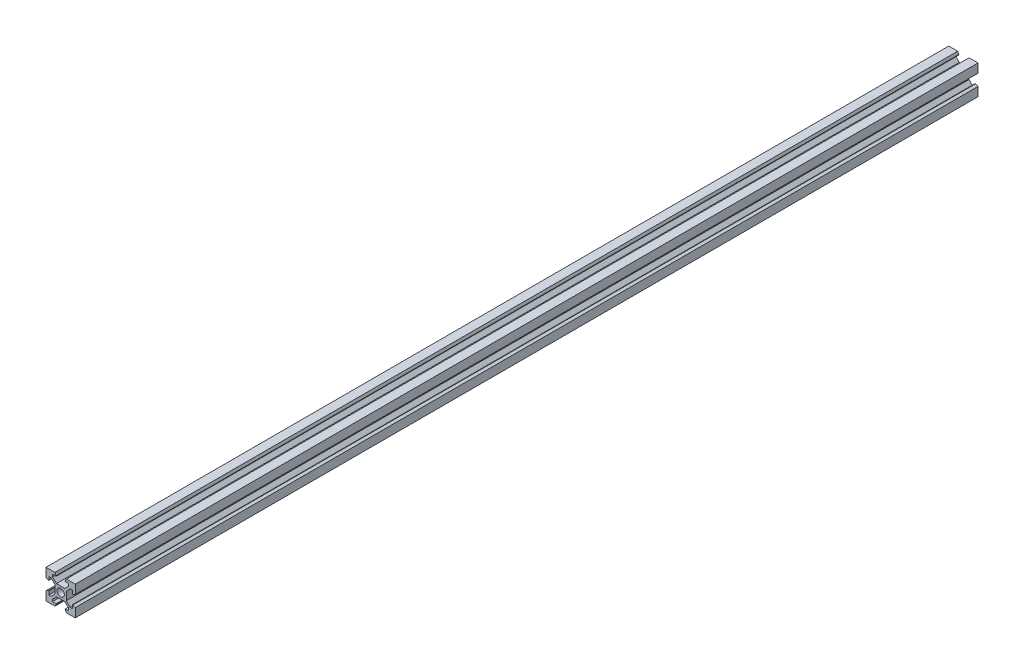
SolidWorks part; units mm, degrees
ref_plane "Front Plane" through (0, 0, 0) normal (0, 0, 1) x (1, 0, 0)
ref_plane "Top Plane" through (0, 0, 0) normal (0, 1, 0) x (1, 0, 0)
ref_plane "Right Plane" through (0, 0, 0) normal (1, 0, 0) x (0, 0, -1)
sketch "Sketch1" plane through (0, 0, 0) normal (0, 0, 1) x (1, 0, 0)
  line L0 (0, 20) -> (0, 13.8958)
  line L1 (0, 0) -> (20, 0)
  line L2 (0, 0) -> (0, 20)
  line L3 (0, 20) -> (20, 20)
  line L4 (20, 0) -> (20, 20)
  line L5 (0, 13.8958) -> (1.56, 13.1)
  line L6 (1.56, 13.1) -> (1.9, 13.1)
  line L7 (1.9, 13.1) -> (1.9, 15.5)
  line L8 (1.9, 15.5) -> (3.4393, 15.5)
  line L9 (3.4393, 15.5) -> (6.2656, 12.6737)
  line L10 (6.2656, 12.6737) -> (7.3263, 13.7344)
  line L11 (7.3263, 13.7344) -> (4.5, 16.5607)
  line L12 (4.5, 16.5607) -> (4.5, 18.1)
  line L13 (4.5, 18.1) -> (6.9, 18.1)
  line L14 (6.9, 18.1) -> (6.9, 18.44)
  line L15 (6.9, 18.44) -> (6.1, 20)
  line L16 (6.1, 20) -> (0, 20)
  line L17 (10, 10) -> (6.1, 13.9)
  line L18 (6.1, 6.1) -> (13.9, 6.1)
  line L19 (6.1, 6.1) -> (6.1, 13.9)
  line L20 (6.1, 13.9) -> (13.9, 13.9)
  line L21 (13.9, 6.1) -> (13.9, 13.9)
  line L22 (6.796, 13.204) -> (4.0494, 15.9506)
  line L23 (10, 10) -> (10, 24.9145) construction
  line L24 (13.1, 18.44) -> (13.9, 20)
  line L25 (13.1, 18.1) -> (13.1, 18.44)
  line L26 (15.5, 18.1) -> (13.1, 18.1)
  line L27 (15.5, 16.5607) -> (15.5, 18.1)
  line L28 (12.6737, 13.7344) -> (15.5, 16.5607)
  line L29 (13.7344, 12.6737) -> (12.6737, 13.7344)
  line L30 (16.5607, 15.5) -> (13.7344, 12.6737)
  line L31 (18.1, 15.5) -> (16.5607, 15.5)
  line L32 (18.1, 13.1) -> (18.1, 15.5)
  line L33 (18.44, 13.1) -> (18.1, 13.1)
  line L34 (20, 13.8958) -> (18.44, 13.1)
  line L35 (10, 10) -> (22.1718, 10)
  line L36 (20, 6.1042) -> (18.44, 6.9)
  line L37 (18.44, 6.9) -> (18.1, 6.9)
  line L38 (18.1, 6.9) -> (18.1, 4.5)
  line L39 (18.1, 4.5) -> (16.5607, 4.5)
  line L40 (16.5607, 4.5) -> (13.7344, 7.3263)
  line L41 (13.7344, 7.3263) -> (12.6737, 6.2656)
  line L42 (12.6737, 6.2656) -> (15.5, 3.4393)
  line L43 (15.5, 3.4393) -> (15.5, 1.9)
  line L44 (15.5, 1.9) -> (13.1, 1.9)
  line L45 (13.1, 1.9) -> (13.1, 1.56)
  line L46 (13.1, 1.56) -> (13.9, 0)
  line L47 (6.9, 1.56) -> (6.1, 0)
  line L48 (6.9, 1.9) -> (6.9, 1.56)
  line L49 (4.5, 1.9) -> (6.9, 1.9)
  line L50 (4.5, 3.4393) -> (4.5, 1.9)
  line L51 (7.3263, 6.2656) -> (4.5, 3.4393)
  line L52 (6.2656, 7.3263) -> (7.3263, 6.2656)
  line L53 (3.4393, 4.5) -> (6.2656, 7.3263)
  line L54 (1.9, 4.5) -> (3.4393, 4.5)
  line L55 (1.9, 6.9) -> (1.9, 4.5)
  line L56 (1.56, 6.9) -> (1.9, 6.9)
  line L57 (0, 6.1042) -> (1.56, 6.9)
  circle A0 centre (10, 10) radius 2.5
  point P21 (2.6697, 15.5)
  dimension "D3" = 5
  dimension "D1" = 20
  dimension "D2" = 20
  dimension "D4" = 10
  dimension "D5" = 10
  dimension "D6" = 7.8
  dimension "D7" = 7.8
  dimension "D8" = 6.1
  dimension "D9" = 6.1
  dimension "D10" = 6.9
  dimension "D11" = 6.9
  dimension "D12" = 6.1042
  dimension "D13" = 6.1
  dimension "D14" = 0.34
  dimension "D15" = 0.34
  dimension "D16" = 1.9
  dimension "D17" = 4.5
  dimension "D18" = 4.5
  dimension "D19" = 1.5
  dimension "D20" = 1.9
extrude "Boss-Extrude1" add sketch "Sketch1" along normal blind 617.1
